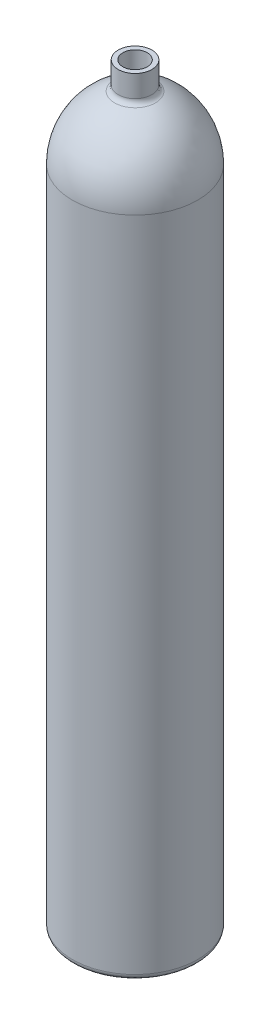
SolidWorks part; units mm, degrees
ref_plane "Front Plane" through (0, 0, 0) normal (0, 0, 1) x (1, 0, 0)
ref_plane "Top Plane" through (0, 0, 0) normal (0, 1, 0) x (1, 0, 0)
ref_plane "Right Plane" through (0, 0, 0) normal (1, 0, 0) x (0, 0, -1)
sketch "Sketch1" plane through (0, 0, 0) normal (0, 1, 0) x (1, 0, 0)
  circle A0 centre (0, 0) radius 53.975
  circle A1 centre (0, 0) radius 49.975
  dimension "D1" = 107.95
  dimension "D2" = 4
extrude "Boss-Extrude1" add sketch "Sketch1" along normal mid plane 567.5
sketch "Sketch2" plane through (0, -283.75, 0) normal (0, -1, 0) x (1, 0, 0)
  circle A0 centre (0, 0) radius 53.975 construction
  circle A1 centre (0, 0) radius 53.975
extrude "Boss-Extrude2" add sketch "Sketch2" along normal blind 4
sketch "Sketch3" plane through (0, 0, 0) normal (0, 0, 1) x (1, 0, 0)
  line L0 (0, 0) -> (0, 415.31) construction
  line L1 (-14.5202, 339.3125) -> (-14.5202, 361.5375)
  line L2 (-53.975, 283.75) -> (-53.975, -287.75) construction
  line L3 (49.975, 283.75) -> (-49.975, 283.75) construction
  line L4 (-10.5202, 336.3955) -> (-10.5202, 361.5375)
  line L5 (-14.5202, 361.5375) -> (-10.5202, 361.5375)
  line L6 (-53.975, 283.75) -> (-49.975, 283.75)
  arc A0 (-14.5202, 339.3125) -> (-53.975, 283.75) centre (4.8755, 283.75) ccw
  arc A1 (-10.5202, 336.3955) -> (-49.975, 283.75) centre (4.8755, 283.75) ccw
  dimension "D1" = 55.5625
  dimension "D2" = 22.225
  dimension "D3" = 4
revolve "Revolve1" add sketch "Sketch3" angle 360 about L0
fillet "Fillet1" radius 5 3 edges at (0, -283.75, 49.975) (0, -287.75, -53.975) (0, 339.3125, -14.5202)
